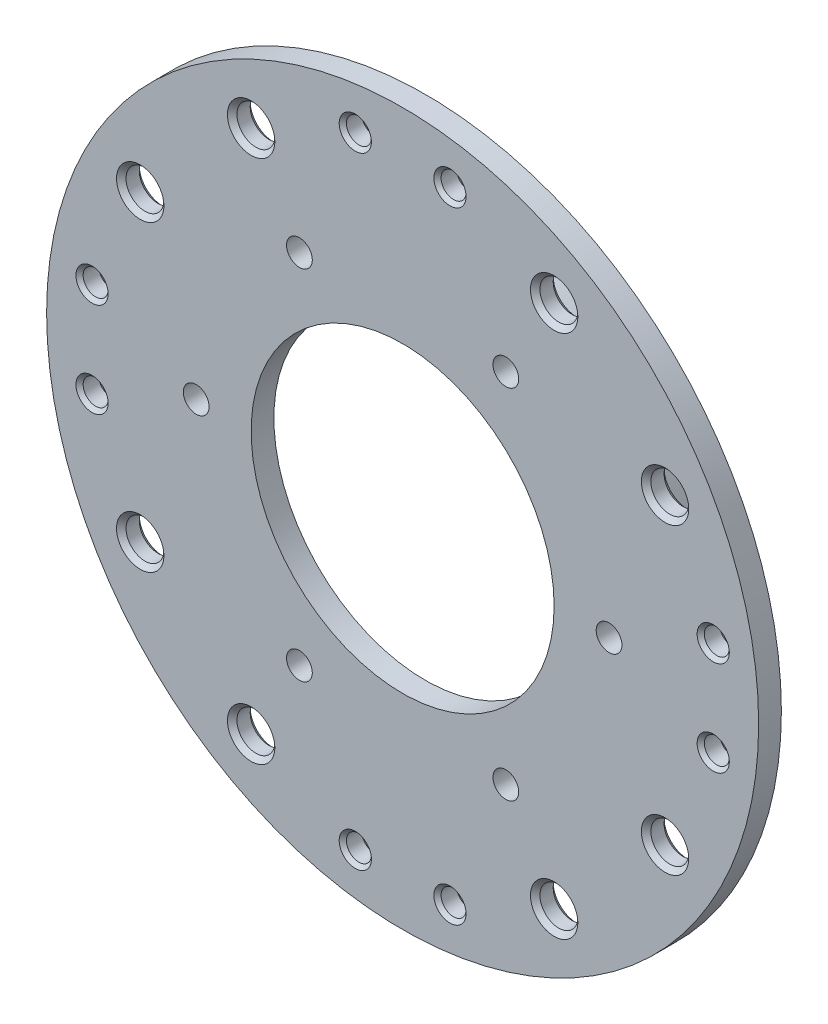
SolidWorks part; units mm, degrees
ref_plane "Plan de face" through (0, 0, 0) normal (0, 0, 1) x (1, 0, 0)
ref_plane "Plan de dessus" through (0, 0, 0) normal (0, 1, 0) x (1, 0, 0)
ref_plane "Plan de droite" through (0, 0, 0) normal (1, 0, 0) x (0, 0, -1)
sketch "Esquisse1" plane through (0, 0, 0) normal (0, 0, 1) x (1, 0, 0)
  circle A0 centre (0, 0) radius 47
  circle A1 centre (0, 0) radius 20
  dimension "D2" = 40
  dimension "D3" = 94
extrude "Boss.-Extru.1" add sketch "Esquisse1" along normal blind 3 from surface at 0.6
sketch "Esquisse2" plane through (0, 0, 0.6) normal (0, 0, -1) x (-1, 0, 0)
  circle A0 centre (0, 0) radius 34.05
  circle A1 centre (0, 0) radius 31.05
  circle A4 centre (0, 0) radius 47 construction
  dimension "D1" = 3
  dimension "D2" = 62.1
extrude "Boss.-Extru.2" add sketch "Esquisse2" along normal blind 8
sketch "Esquisse3" plane through (0, 0, 3.6) normal (0, 0, 1) x (1, 0, 0)
  line L0 (-27.25, 0) -> (27.25, 0) construction
  line L1 (-13.625, -23.5992) -> (13.625, 23.5992) construction
  line L2 (13.625, -23.5992) -> (-13.625, 23.5992) construction
  circle A1 centre (-13.625, -23.5992) radius 1.65
  circle A2 centre (-13.625, 23.5992) radius 1.65
  circle A3 centre (27.25, 0) radius 1.65
  circle A4 centre (0, 0) radius 27.25 construction
  circle A5 centre (13.625, -23.5992) radius 1.65
  circle A6 centre (-27.25, 0) radius 1.65
  circle A7 centre (13.625, 23.5992) radius 1.65
  point P22 (0, 0)
  point P23 (0, 0)
  point P25 (0, 0)
  dimension "D3" = 54.5
  dimension "D6" = 3.3
  dimension "D1" = 60
  dimension "D2" = 60
chamfer "Chanfrein1" distance 0.5 angle 45 2 edges at (-31.05, 0, -7.4) (-34.05, 0, -7.4)
sketch "Esquisse8" plane through (0, 0, 3.6) normal (0, 0, 1) x (1, 0, 0)
  line L0 (0, 0) -> (-47, 0) construction
  line L1 (0, 0) -> (47, 0) construction
  line L2 (0, -47) -> (0, 47) construction
  line L4 (-6.25, 41) -> (6.25, 41) construction
  line L5 (-6.25, 41) -> (-6.25, -41) construction
  line L6 (6.25, 41) -> (6.25, -41) construction
  line L7 (-6.25, -41) -> (6.25, -41) construction
  line L8 (41, 6.25) -> (-41, 6.25) construction
  line L9 (41, 6.25) -> (41, -6.25) construction
  line L10 (-41, 6.25) -> (-41, -6.25) construction
  line L11 (41, -6.25) -> (-41, -6.25) construction
  circle A0 centre (41, 6.25) radius 1.65
  circle A1 centre (-6.25, 41) radius 1.65
  circle A2 centre (6.25, 41) radius 1.65
  circle A3 centre (6.25, -41) radius 1.65
  circle A4 centre (-6.25, -41) radius 1.65
  circle A5 centre (0, 0) radius 47 construction
  circle A7 centre (41, -6.25) radius 1.65
  circle A8 centre (-41, -6.25) radius 1.65
  circle A9 centre (-41, 6.25) radius 1.65
  point P9 (0, 0)
  dimension "D4" = 3.3
  dimension "D5" = 82
  dimension "D6" = 12.5
  dimension "D1" = 41
  dimension "D2" = 12.5
  dimension "D3" = 82
sketch "Esquisse13" plane through (0, 0, 0.6) normal (0, 0, -1) x (-1, 0, 0)
  line L10 (34.641, -20) -> (-34.641, 20) construction
  line L11 (-20, -34.641) -> (20, 34.641) construction
  line L12 (-20, 34.641) -> (20, -34.641) construction
  line L13 (0, 40) -> (0, -40) construction
  line L14 (-40, 0) -> (40, 0) construction
  line L15 (34.641, 20) -> (-34.641, -20) construction
  circle A0 centre (-20, 34.641) radius 2.5
  circle A2 centre (0, 0) radius 40 construction
  circle A4 centre (34.641, 20) radius 2.5
  circle A6 centre (-34.641, -20) radius 2.5
  circle A7 centre (-34.641, 20) radius 2.5
  circle A8 centre (20, 34.641) radius 2.5
  circle A9 centre (34.641, -20) radius 2.5
  circle A10 centre (-20, -34.641) radius 2.5
  circle A12 centre (20, -34.641) radius 2.5
  point P23 (0, 0)
  point P25 (0, 0)
  point P34 (0, 0)
  point P37 (0, 0)
  point P40 (0, 0)
  point P43 (0, 0)
  dimension "D1" = 30
  dimension "D2" = 5
  dimension "D3" = 30
  dimension "D5" = 80
  dimension "D4" = 30
  dimension "D7" = 30
hole_wizard "Trou taraudé M4x0.71" positions "Esquisse3D2" profile "Esquisse15" tap size "M4x0.7" standard "Ansi Metric" end condition through all
sketch3d "Esquisse3D2"
  point P0 (6.25, 41, 3.6)
  point P3 (-6.25, 41, 3.6)
  point P6 (6.25, -41, 3.6)
  point P9 (-6.25, -41, 3.6)
  point P12 (41, 6.25, 3.6)
  point P15 (41, -6.25, 3.6)
  point P18 (-41, -6.25, 3.6)
  point P21 (-41, 6.25, 3.6)
sketch "Esquisse15" plane through (6.25, 41, 3.6) normal (1, 0, 0) x (0, -1, 0)
  line L0 (0, 0) -> (0, 3)
  line L1 (0, 3) -> (2.125, 3)
  line L2 (1.65, 2.525) -> (1.65, 0.475)
  line L3 (1.65, 0.475) -> (2.125, 0)
  line L5 (2.125, 0) -> (0, 0)
  line L6 (-1.65, 0.475) -> (-2.125, 0) construction
  line L7 (2.125, 3) -> (1.65, 2.525)
  line L8 (-2.125, 3) -> (-1.65, 2.525) construction
  line L11 (0, -6.35) -> (0, 107.95) construction
  dimension "Diamètre du trou pour taraudage jusqu'au prochain" = 3.3
  dimension "Profondeur du trou pour taraudage jusqu'au prochain" = 3
  dimension "Diamètre du fraisage entrant" = 4.25
  dimension "Angle du fraisage entrant" = 90
  dimension "Diamètre du fraisage débouchant" = 4.25
  dimension "Angle du fraisage débouchant" = 90
cosmetic thread "Filetage de perçage11" parameters "D2"=4
cosmetic thread "Filetage de perçage12" parameters "D2"=4
cosmetic thread "Filetage de perçage13" parameters "D2"=4
cosmetic thread "Filetage de perçage14" parameters "D2"=4
cosmetic thread "Filetage de perçage19" parameters "D2"=4
cosmetic thread "Filetage de perçage20" parameters "D2"=4
cosmetic thread "Filetage de perçage21" parameters "D2"=4
cosmetic thread "Filetage de perçage22" parameters "D2"=4
hole_wizard "Trou taraudé M6x1.01" positions "Esquisse3D3" profile "Esquisse17" tap size "M6x1.0" standard "Ansi Metric" end condition through all
sketch3d "Esquisse3D3"
  point P0 (34.641, 20, 0.6)
  point P3 (20, 34.641, 0.6)
  point P6 (-20, 34.641, 0.6)
  point P9 (-34.641, 20, 0.6)
  point P12 (-34.641, -20, 0.6)
  point P15 (-20, -34.641, 0.6)
  point P18 (20, -34.641, 0.6)
  point P21 (34.641, -20, 0.6)
sketch "Esquisse17" plane through (34.641, 20, 0.6) normal (1, 0, 0) x (0, 1, 0)
  line L0 (0, 0) -> (0, 3)
  line L1 (0, 3) -> (3.125, 3)
  line L2 (2.5, 2.375) -> (2.5, 0.625)
  line L3 (2.5, 0.625) -> (3.125, 0)
  line L5 (3.125, 0) -> (0, 0)
  line L6 (-2.5, 0.625) -> (-3.125, 0) construction
  line L7 (3.125, 3) -> (2.5, 2.375)
  line L8 (-3.125, 3) -> (-2.5, 2.375) construction
  line L11 (0, -6.35) -> (0, 107.95) construction
  dimension "Diamètre du trou pour taraudage jusqu'au prochain" = 5
  dimension "Profondeur du trou pour taraudage jusqu'au prochain" = 3
  dimension "Diamètre du fraisage entrant" = 6.25
  dimension "Angle du fraisage entrant" = 90
  dimension "Diamètre du fraisage débouchant" = 6.25
  dimension "Angle du fraisage débouchant" = 90
cosmetic thread "Filetage de perçage31" parameters "D2"=6
cosmetic thread "Filetage de perçage32" parameters "D2"=6
cosmetic thread "Filetage de perçage33" parameters "D2"=6
cosmetic thread "Filetage de perçage34" parameters "D2"=6
cosmetic thread "Filetage de perçage35" parameters "D2"=6
cosmetic thread "Filetage de perçage36" parameters "D2"=6
cosmetic thread "Filetage de perçage37" parameters "D2"=6
cosmetic thread "Filetage de perçage38" parameters "D2"=6
hole_wizard "Dégagement M31" positions "Esquisse3D4" profile "Esquisse22" hole size "M3" standard "Ansi Metric" end condition up to next
sketch3d "Esquisse3D4"
  point P0 (27.25, 0, 3.6)
  point P3 (13.625, 23.5992, 3.6)
  point P6 (-13.625, 23.5992, 3.6)
  point P9 (-27.25, 0, 3.6)
  point P12 (-13.625, -23.5992, 3.6)
  point P15 (13.625, -23.5992, 3.6)
sketch "Esquisse22" plane through (27.25, 0, 3.6) normal (1, 0, 0) x (0, -1, 0)
  line L0 (0, 0) -> (0, 3)
  line L1 (0, 3) -> (1.7, 3)
  line L2 (1.7, 3) -> (1.7, 0)
  line L5 (1.7, 0) -> (0, 0)
  line L11 (0, -6.35) -> (0, 107.95) construction
  dimension "Diamètre du perçage jusqu'au prochain" = 3.4
  dimension "Profondeur du perçage jusqu'au prochain" = 3
